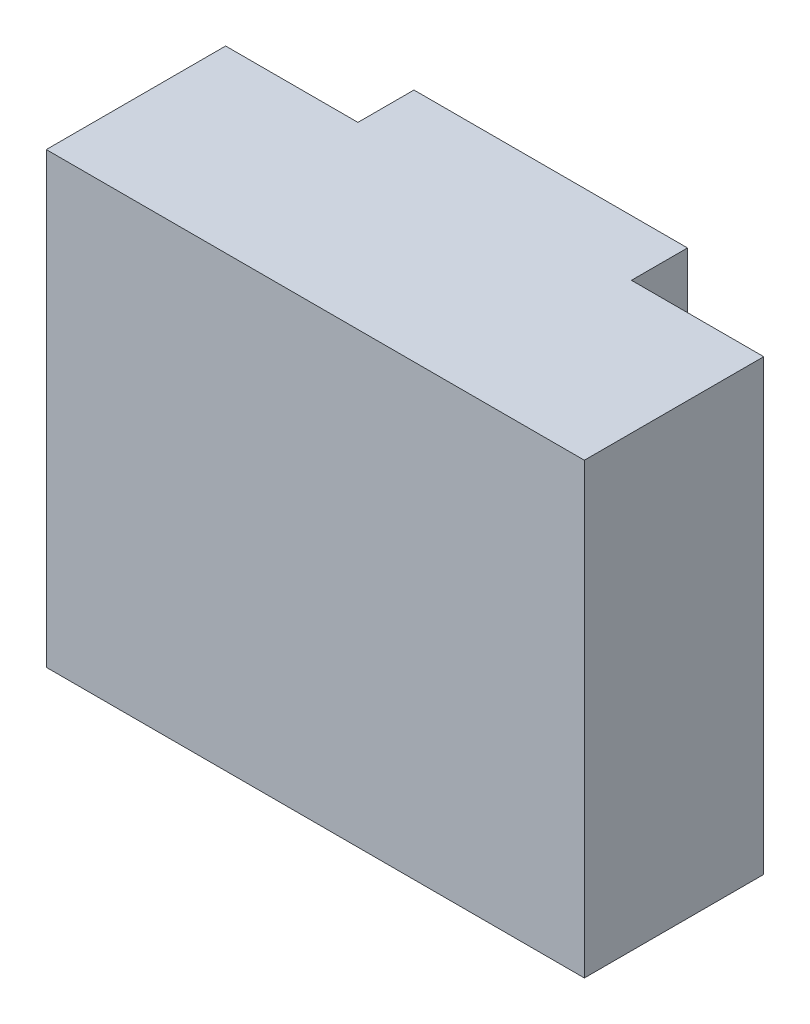
SolidWorks part; units mm, degrees
ref_plane "Front Plane" through (0, 0, 0) normal (0, 0, 1) x (1, 0, 0)
ref_plane "Top Plane" through (0, 0, 0) normal (0, 1, 0) x (1, 0, 0)
ref_plane "Right Plane" through (0, 0, 0) normal (1, 0, 0) x (0, 0, -1)
sketch "Sketch1" plane through (0, 0, 0) normal (0, 1, 0) x (1, 0, 0)
  line L0 (0, 0) -> (0, 38.9104) construction
  line L1 (-12, 0) -> (12, 0)
  line L2 (12, 0) -> (12, 8)
  line L3 (12, 8) -> (6.1, 8)
  line L4 (6.1, 8) -> (6.1, 10.5)
  line L5 (6.1, 10.5) -> (-6.1, 10.5)
  line L6 (-12, 0) -> (-12, 8)
  line L7 (-12, 8) -> (-6.1, 8)
  line L8 (-6.1, 8) -> (-6.1, 10.5)
  point P12 (0, 10.5)
  dimension "D1" = 2.5
  dimension "D2" = 8
  dimension "D3" = 12
  dimension "D4" = 6.1
extrude "Boss-Extrude1" add sketch "Sketch1" along normal blind 20
